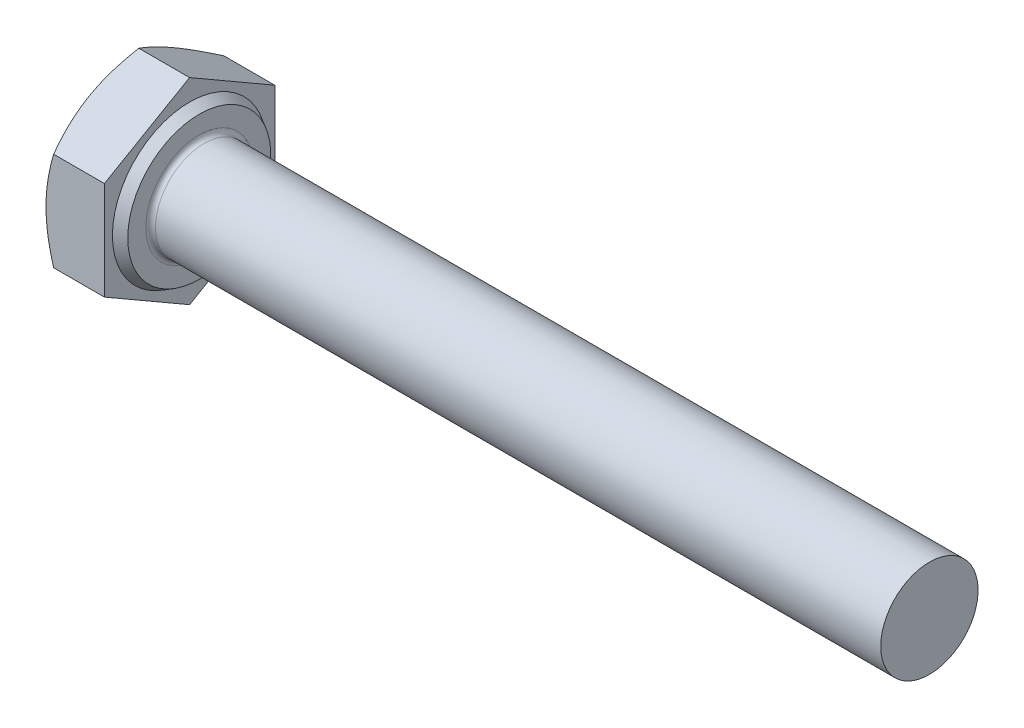
SolidWorks part; units mm, degrees
ref_plane "前视" through (0, 0, 0) normal (0, 0, 1) x (1, 0, 0)
ref_plane "上视" through (0, 0, 0) normal (0, 1, 0) x (1, 0, 0)
ref_plane "右视" through (0, 0, 0) normal (1, 0, 0) x (0, 0, -1)
sketch "草图1" plane through (0, 0, 0) normal (1, 0, 0) x (0, 0, -1)
  line L0 (3.5, 2.0207) -> (3.5, -2.0207)
  line L1 (-3.5, 2.0207) -> (-3.5, -2.0207)
  line L2 (3.5, -2.0207) -> (0, -4.0415)
  line L3 (0, -4.0415) -> (-3.5, -2.0207)
  line L4 (3.5, 2.0207) -> (0, 4.0415)
  line L5 (0, 4.0415) -> (-3.5, 2.0207)
  circle A0 centre (0, 0) radius 3.83 construction
  dimension "e" = 7.66
  dimension "s" = 7
  dimension "D2" = 120
  dimension "D3" = 3.5
  dimension "D4" = 3.5
  dimension "D5" = 3.5
extrude "基体-拉伸" add sketch "草图1" along normal blind 2.8
sketch "草图2" plane through (0, 0, 0) normal (0, 0, 1) x (1, 0, 0)
  line L0 (0, 2.0207) -> (0, -2.0207) construction
  line L1 (0, 0) -> (32.8, 0)
  line L2 (0, 0) -> (0, 2)
  line L3 (0, 2) -> (18.8, 2)
  line L4 (32.8, 0) -> (32.8, 1.3938)
  line L5 (2.8, 4.0415) -> (2.8, 2.0207) construction
  line L7 (0, 0) -> (36.8, 0) construction
  line L8 (32.8, -1.3938) -> (18.8, -2) construction
  line L9 (0, -2) -> (18.8, -2) construction
  line L10 (3.5, 2) -> (3.5, 0) construction
  line L11 (18.8, 15.24) -> (18.8, -1.27) construction
  line L12 (2.8, 2.0207) -> (2.8, -2.0207) construction
  line L13 (18.8, 2) -> (32.8, 2)
  line L14 (32.8, 2) -> (32.8, 1.3938)
  dimension "l" = 30
  dimension "d" = 4
  dimension "Minor_dia" = 2.7876
  dimension "p" = 0.7
  dimension "b" = 14
  dimension "ds" = 4
revolve "凸台-旋转1" add sketch "草图2" angle 360 about L7
cosmetic thread "螺旋线1" parameters "Thread_length"=14, "Thread_minor"=2.7876
sketch "草图3" plane through (0, 0, 0) normal (0, 0, 1) x (1, 0, 0)
  line L0 (0, 3.5) -> (3.1994, 9.0415)
  line L1 (0, 4.0415) -> (0, 2.0207) construction
  line L2 (3.1994, 9.0415) -> (3.1994, 14.0415)
  line L3 (3.1994, 14.0415) -> (-10, 14.0415)
  line L4 (-10, 14.0415) -> (-10, 3.5)
  line L5 (-10, 3.5) -> (0, 3.5)
  line L6 (0, 0) -> (99.06, 0) construction
  line L7 (2.8, 4.0415) -> (0, 4.0415) construction
  dimension "D1" = 3.5
  dimension "D2" = 5
  dimension "D3" = 10
  dimension "D4" = 5
  dimension "Head_ch_ang" = 30
revolve "切除-旋转1" cut sketch "草图3" angle 360 about L6
sketch "草图4" plane through (0, 0, 0) normal (0, 0, 1) x (1, 0, 0)
  line L0 (2.8, 0) -> (2.8, 2.94) construction
  line L2 (2.8, -2) -> (2.8, 2) construction
  line L3 (2.8, 4.0415) -> (2.8, 2.0207) construction
  line L4 (2.8, 2.94) -> (2.4, 3.1709)
  line L5 (0, 0) -> (95.25, 0) construction
  line L6 (0, 0) -> (36.8, 0) construction
  line L9 (2.4, 3.1709) -> (2.4, 4.0415)
  line L10 (2.8, 4.0415) -> (0.3126, 4.0415) construction
  line L11 (2.4, 4.0415) -> (2.8, 4.0415)
  line L12 (2.8, 4.0415) -> (2.8, 2.94)
  dimension "D1" = 120
  dimension "c" = 0.4
  dimension "dw" = 5.88
revolve "切除-旋转3" cut sketch "草图4" angle 360 about L5
fillet "圆角" radius 0.2 1 edges at (2.8, 0, -2)
sketch "草图6" plane through (0, 0, 0) normal (0, 0, 1) x (1, 0, 0)
  line L0 (0, 0) -> (32.8, 0) construction
  line L1 (32.8, -2) -> (32.8, 2) construction
  line L2 (32.8, 0) -> (32.8, 2) construction
  line L4 (32.45, 2) -> (33.15, 2)
  line L5 (32.45, 2) -> (32.8, 1.3938)
  line L6 (32.8, 1.3938) -> (33.15, 2)
  dimension "D1" = 0.7
revolve "切除-旋转4" [suppressed] cut sketch "草图6" angle 360 about L0
pattern_linear "阵列(线性)1" [suppressed]
